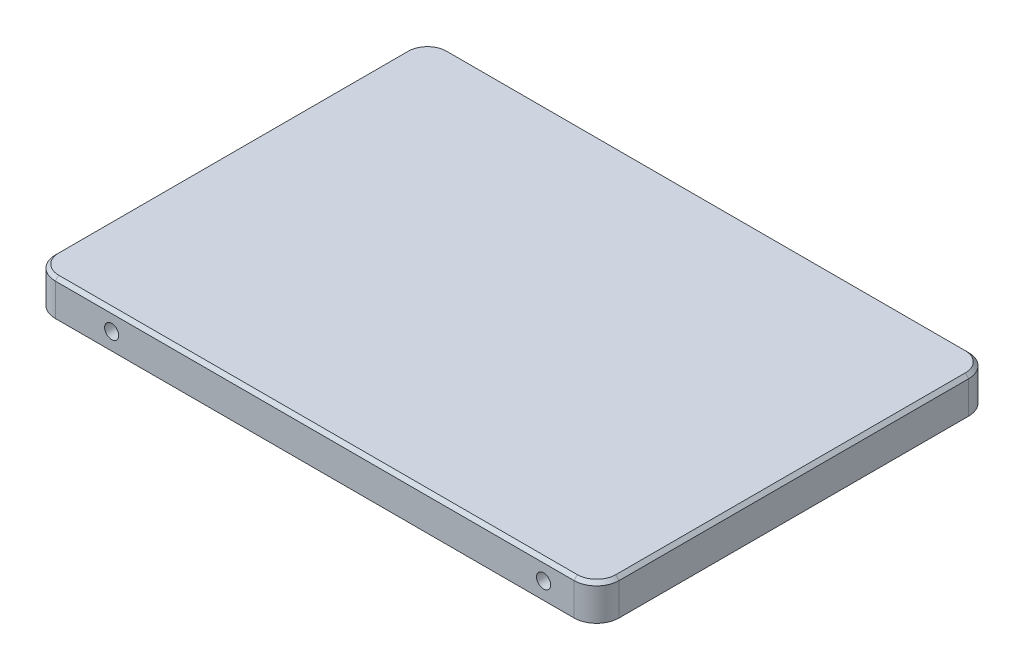
SolidWorks part; units mm, degrees
ref_plane "Front Plane" through (0, 0, 0) normal (0, 0, 1) x (1, 0, 0)
ref_plane "Top Plane" through (0, 0, 0) normal (0, 1, 0) x (1, 0, 0)
ref_plane "Right Plane" through (0, 0, 0) normal (1, 0, 0) x (0, 0, -1)
sketch "Sketch1" plane through (0, 0, 0) normal (0, 1, 0) x (1, 0, 0)
  line L1 (-46, -35) -> (46, -35)
  line L2 (-50, -31) -> (-50, 31)
  line L3 (-46, 35) -> (46, 35)
  line L4 (50, -31) -> (50, 31)
  line L5 (-50, -35) -> (50, 35) construction
  line L6 (-50, 35) -> (50, -35) construction
  arc A0 (-50, -31) -> (-46, -35) centre (-46, -31) ccw
  arc A1 (46, -35) -> (50, -31) centre (46, -31) ccw
  arc A2 (50, 31) -> (46, 35) centre (46, 31) ccw
  arc A3 (-46, 35) -> (-50, 31) centre (-46, 31) ccw
  point P0 (0, 0)
  dimension "D3" = 4
  dimension "D1" = 70
  dimension "D2" = 100
extrude "Boss-Extrude1" add sketch "Sketch1" along normal blind 6.35
sketch "Sketch2" plane through (0, 0, 0) normal (0, -1, 0) x (1, 0, 0)
  line L0 (-50, -31) -> (-50, 31) construction
  line L1 (-50, -24) -> (-45, -24)
  line L2 (-50, -24) -> (-50, 13.5)
  line L3 (-50, 13.5) -> (-45, 13.5)
  line L4 (-45, -24) -> (-45, 13.5)
  line L5 (46, -35) -> (-46, -35) construction
  dimension "D1" = 37.5
  dimension "D2" = 11
  dimension "D3" = 5
extrude "Cut-Extrude1" cut sketch "Sketch2" against normal blind 5
sketch "Sketch3" plane through (-50, 0, 0) normal (-1, 0, 0) x (0, 0, 1)
  line L0 (-24, 5) -> (-24, 0) construction
  line L1 (-24, 0.6) -> (-26, 0.6)
  line L2 (-24, 0.6) -> (-24, 3.35)
  line L3 (-24, 3.35) -> (-26, 3.35)
  line L4 (-26, 0.6) -> (-26, 3.35)
  line L5 (13.5, 5) -> (13.5, 0) construction
  line L6 (13.5, 0.6) -> (15.5, 0.6)
  line L7 (13.5, 0.6) -> (13.5, 3.35)
  line L8 (13.5, 3.35) -> (15.5, 3.35)
  line L9 (15.5, 0.6) -> (15.5, 3.35)
  line L11 (-31, 6.35) -> (31, 6.35) construction
  dimension "D1" = 3
  dimension "D2" = 2.75
  dimension "D3" = 2
  dimension "D4" = 2
extrude "Cut-Extrude2" cut sketch "Sketch3" against normal up to surface (5 mm away) up to face at (-45, 2.5, -5.25)
sketch "Sketch4" plane through (-45, 0, 0) normal (-1, 0, 0) x (0, 0, 1)
  line L0 (-24, 5) -> (-24, 3.35) construction
  line L1 (-22, 3) -> (-2, 3)
  line L2 (-22, 3) -> (-22, 2)
  line L3 (-22, 2) -> (-2, 2)
  line L4 (-2, 3) -> (-2, 2)
  line L5 (2, 3) -> (11.5, 3)
  line L6 (2, 3) -> (2, 2)
  line L7 (2, 2) -> (11.5, 2)
  line L8 (11.5, 3) -> (11.5, 2)
  line L9 (-2, 3) -> (-1, 3)
  line L10 (-2, 3) -> (-2, 1.25)
  line L11 (-2, 1.25) -> (-1, 1.25)
  line L12 (-1, 3) -> (-1, 1.25)
  line L13 (2, 3) -> (1, 3)
  line L14 (2, 3) -> (2, 1.25)
  line L15 (2, 1.25) -> (1, 1.25)
  line L16 (1, 3) -> (1, 1.25)
  line L17 (13.5, 5) -> (13.5, 3.35) construction
  line L18 (-24, 0) -> (13.5, 0) construction
  point P20 (-2, 2.5)
  dimension "D1" = 1
  dimension "D2" = 1.75
  dimension "D3" = 1
  dimension "D4" = 1
  dimension "D5" = 2
  dimension "D6" = 2
  dimension "D7" = 20
  dimension "D8" = 2
  dimension "D9" = 10.5
extrude "Boss-Extrude2" add sketch "Sketch4" along normal up to surface (5 mm away) contours L4 L1 L2 L3 | L12 L9 L4 L10 L11 | L13 L16 L15 L14 L6 | L8 L5 L6 L7 up to face at (-50, 2.4063, -3.9375)
sketch "Sketch5" plane through (0, 0, 0) normal (0, -1, 0) x (1, 0, 0)
  line L0 (-37.25, 30.86) -> (-37.25, -30.86) construction
  line L1 (-36, -32.11) -> (40.6, -32.11) construction
  line L2 (41.85, -30.86) -> (41.85, 30.86) construction
  line L3 (40.6, 32.11) -> (-36, 32.11) construction
  line L6 (-50, -31) -> (-50, -24) construction
  line L7 (-37.25, 0) -> (-29.9091, 0) construction
  line L8 (50, 0) -> (46.2578, 0) construction
  line L9 (50, 31) -> (50, -31) construction
  circle A0 centre (-36, 30.86) radius 1.25
  circle A1 centre (40.6, 30.86) radius 1.25
  circle A2 centre (40.6, -30.86) radius 1.25
  circle A3 centre (-36, -30.86) radius 1.25
  dimension "D1" = 2.5
  dimension "D2" = 2.5
  dimension "D3" = 2.5
  dimension "D4" = 2.5
  dimension "D5" = 76.6
  dimension "D6" = 14
  dimension "D7" = 61.72
extrude "Cut-Extrude3" cut sketch "Sketch5" against normal blind 5
sketch "Sketch6" plane through (0, 0, -35) normal (0, 0, -1) x (-1, 0, 0)
  line L0 (-39.35, 3) -> (34.75, 3) construction
  line L1 (-46, 0) -> (46, 0) construction
  line L2 (50, 6.35) -> (50, 0) construction
  circle A0 centre (-40.6, 3) radius 1.25
  circle A1 centre (36, 3) radius 1.25
  dimension "D1" = 2.5
  dimension "D2" = 2.5
  dimension "D3" = 3
  dimension "D4" = 76.6
  dimension "D5" = 14
extrude "Cut-Extrude4" cut sketch "Sketch6" against normal blind 6
mirror "Mirror1" about plane through (0, 0, 0) normal (0, 0, 1) of "Cut-Extrude4"
chamfer "Chamfer1" distance 0.6 angle 45 8 edges at (0, 6.35, 35) (48.8284, 6.35, 33.8284) (-48.8284, 6.35, 33.8284) (50, 6.35, 0) (-50, 6.35, 0) (48.8284, 6.35, -33.8284) (-48.8284, 6.35, -33.8284) (0, 6.35, -35)
